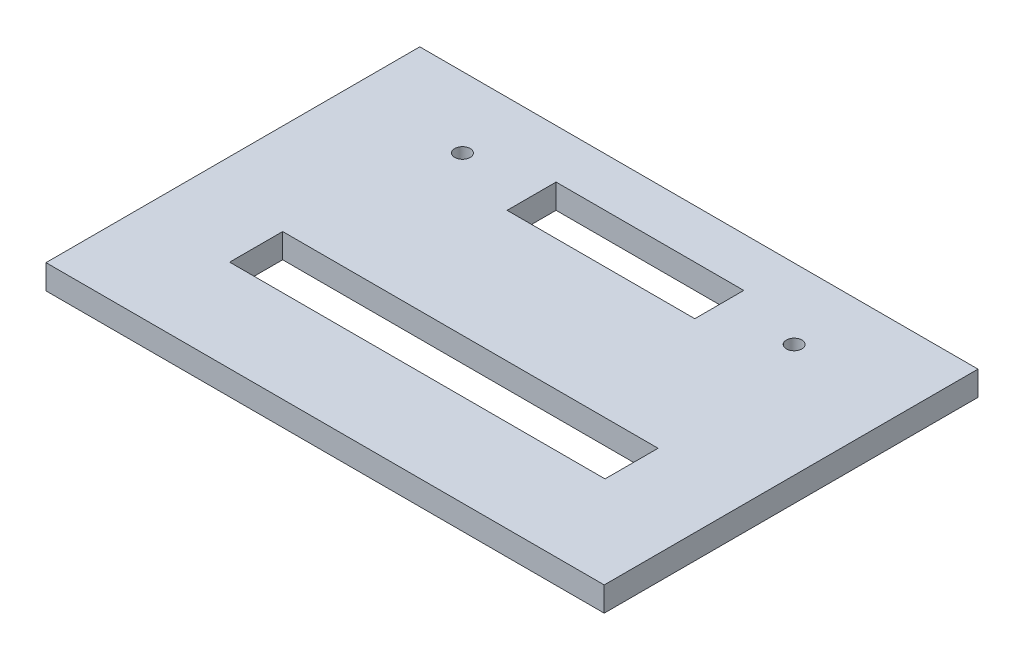
SolidWorks part; units mm, degrees
material "ABS"
ref_plane "Front Plane" through (0, 0, 0) normal (0, 0, 1) x (1, 0, 0)
ref_plane "Top Plane" through (0, 0, 0) normal (0, 1, 0) x (1, 0, 0)
ref_plane "Right Plane" through (0, 0, 0) normal (1, 0, 0) x (0, 0, -1)
sketch "Sketch1" plane through (0, 0, 0) normal (0, 1, 0) x (1, 0, 0)
  line L1 (-34.2, -22.9) -> (34.2, -22.9)
  line L2 (-34.2, -22.9) -> (-34.2, 22.9)
  line L3 (-34.2, 22.9) -> (34.2, 22.9)
  line L4 (34.2, -22.9) -> (34.2, 22.9)
  line L5 (-34.2, -22.9) -> (34.2, 22.9) construction
  line L6 (-34.2, 22.9) -> (34.2, -22.9) construction
  point P0 (0, 0)
  dimension "D1" = 45.8
  dimension "D2" = 68.4
extrude "Boss-Extrude1" add sketch "Sketch1" along normal blind 3
sketch "Sketch2" plane through (0, 3, 0) normal (0, 1, 0) x (1, 0, 0)
  line L0 (34.2, 22.9) -> (-34.2, 22.9) construction
  line L1 (0, 0) -> (0, 22.9) construction
  circle A0 centre (-20.32, 14.25) radius 0.95
  circle A1 centre (20.32, 14.25) radius 0.95
  dimension "D1" = 1.9
  dimension "D2" = 8.65
  dimension "D3" = 20.32
extrude "Cut-Extrude1" cut sketch "Sketch2" against normal through all
sketch "Sketch3" plane through (0, 3, 0) normal (0, 1, 0) x (1, 0, 0)
  line L0 (34.2, 22.9) -> (-34.2, 22.9) construction
  line L1 (11.5, 16.9) -> (-11.5, 16.9)
  line L2 (11.5, 16.9) -> (11.5, 10.9)
  line L3 (11.5, 10.9) -> (-11.5, 10.9)
  line L4 (-11.5, 16.9) -> (-11.5, 10.9)
  line L6 (23, -5.1) -> (-23, -5.1)
  line L7 (23, -5.1) -> (23, -11.6)
  line L8 (23, -11.6) -> (-23, -11.6)
  line L9 (-23, -5.1) -> (-23, -11.6)
  point P10 (0, 10.9)
  point P12 (0, -5.1)
  dimension "D1" = 6
  dimension "D2" = 6
  dimension "D3" = 22
  dimension "D4" = 28.5
  dimension "D5" = 46
  dimension "D6" = 23
extrude "Cut-Extrude2" cut sketch "Sketch3" against normal through all
equation "\"smallPulleyTeeth\"= 30"
equation "\"largePulleyTeeth\"= 30"
equation "\"eighthThick\"= 3.0mm"
equation "\"sixteenthThick\"= 1.7mm"
equation "\"quarterThick\"=6.0mm"
equation "\"OD\"= 145mm"
equation "\"puckAngle\"= 60.5deg"
equation "\"puckDiam\"= 76.5mm"
equation "\"puckDist\"= 85mm"
equation "\"scoopFillet\"= 5mm"
equation "\"axlePress\"= 5.9mm"
equation "\"press\"= 0.2mm"
equation "\"wheelClear\"= 0.3mm"
equation "\"10-32clear\"= 4.8mm"
equation "\"10-32tap\"= 4.45mm"
equation "\"6-32clear\"= 3.3mm"
equation "\"8-32clear\"= 4.0mm"
equation "\"4-40clear\"= 3.0mm"
equation "\"wheelHeight\"= 22mm"
equation "\"wheelWell\"= 65mm"
equation "\"ledSmall\"= 3.1mm"
equation "\"ledLarge\"= 4.2mm"
equation "\"ledLength\"= 4.2mm"
equation "\"4-40close\"= 2.7mm"
equation "\"4-40nutThick\"= 2.2mm"
equation "\"4-40nutWidth\"= 6.2mm"
equation "\"4-40insertHeight\"= 3.5mm"
equation "\"4-40insert\"= 4.25mm"
equation "\"D1@Boss-Extrude1\"=\"eighthThick\""
